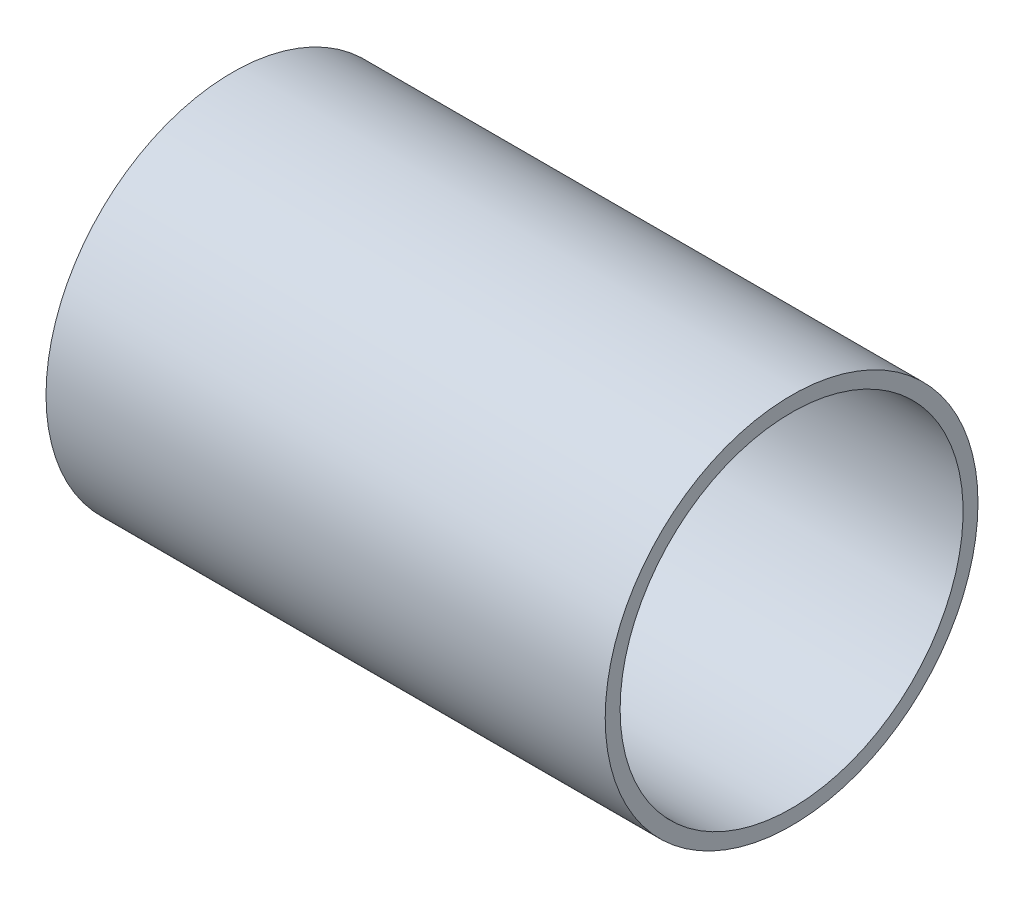
SolidWorks part; units mm, degrees
material "Galvanized Steel"
ref_plane "Front Plane" through (0, 0, 0) normal (0, 0, 1) x (1, 0, 0)
ref_plane "Top Plane" through (0, 0, 0) normal (0, 1, 0) x (1, 0, 0)
ref_plane "Right Plane" through (0, 0, 0) normal (1, 0, 0) x (0, 0, -1)
sketch "Sketch1" plane through (0, 0, 0) normal (1, 0, 0) x (0, 0, -1)
  circle A0 centre (0, 0) radius 15
  circle A1 centre (0, 0) radius 13.8
  dimension "D1" = 30
  dimension "D2" = 27.6
extrude "Boss-Extrude1" add sketch "Sketch1" along normal blind 45
